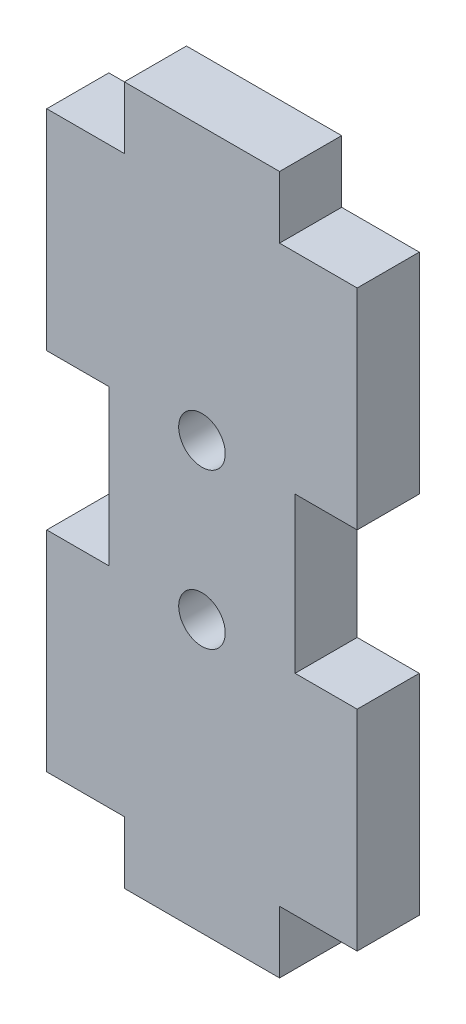
SolidWorks part; units mm, degrees
ref_plane "Спереди" through (0, 0, 0) normal (0, 0, 1) x (1, 0, 0)
ref_plane "Сверху" through (0, 0, 0) normal (0, 1, 0) x (1, 0, 0)
ref_plane "Справа" through (0, 0, 0) normal (1, 0, 0) x (0, 0, -1)
other "Configuration Table"
sketch "Эскиз1" plane through (0, 0, 0) normal (0, 0, 1) x (1, 0, 0)
  line L0 (10, 37) -> (10, -15) construction
  line L1 (0, 0) -> (5, 0)
  line L2 (0, 0) -> (0, 13.5)
  line L3 (0, 37) -> (5, 37)
  line L4 (20, 0) -> (20, 13.5)
  line L5 (5, 37) -> (5, 41)
  line L6 (5, 41) -> (15, 41)
  line L7 (15, 37) -> (15, 41)
  line L8 (15, 37) -> (20, 37)
  line L9 (0, 18.5) -> (20, 18.5) construction
  line L10 (15, 0) -> (15, -4)
  line L11 (5, -4) -> (15, -4)
  line L12 (5, 0) -> (5, -4)
  line L13 (15, 0) -> (20, 0)
  line L14 (0, 23.5) -> (4, 23.5)
  line L15 (4, 23.5) -> (4, 13.5)
  line L16 (0, 13.5) -> (4, 13.5)
  line L17 (20, 13.5) -> (16, 13.5)
  line L18 (16, 23.5) -> (16, 13.5)
  line L19 (20, 23.5) -> (16, 23.5)
  line L20 (0, 23.5) -> (0, 37)
  line L21 (20, 23.5) -> (20, 37)
  circle A0 centre (10, 23.5) radius 1.5
  circle A1 centre (10, 13.5) radius 1.5
  point P11 (10, 41)
  point P22 (4, 18.5)
  dimension "D7" = 3
  dimension "D1" = 37
  dimension "D2" = 20
  dimension "D3" = 4
  dimension "D4" = 10
  dimension "D5" = 4
  dimension "D6" = 10
  dimension "D8" = 10
extrude "Бобышка-Вытянуть1" add sketch "Эскиз1" along normal blind 4
